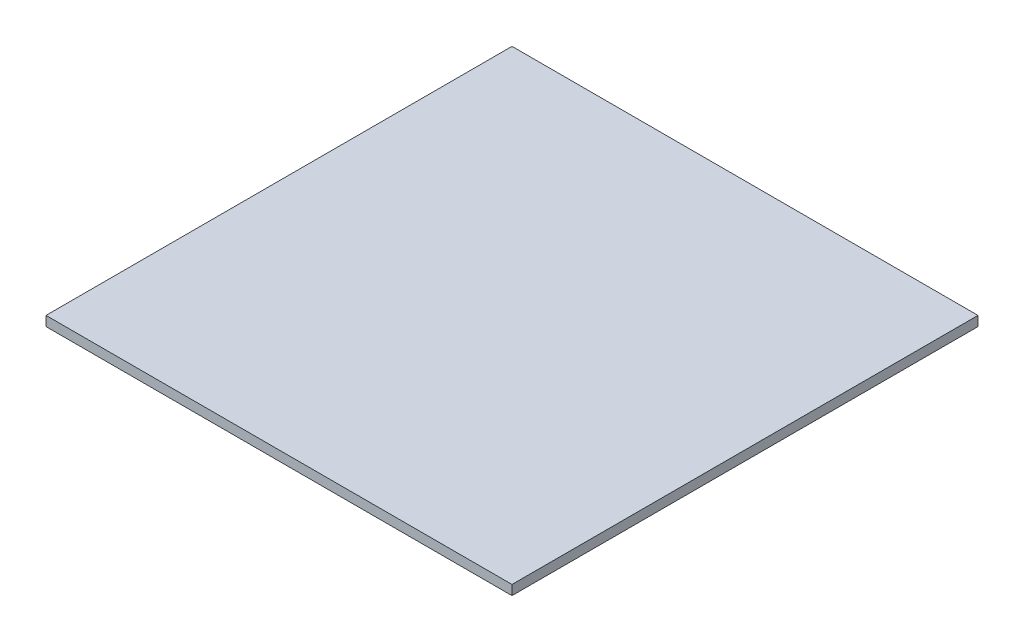
SolidWorks part; units mm, degrees
ref_plane "Front Plane" through (0, 0, 0) normal (0, 0, 1) x (1, 0, 0)
ref_plane "Top Plane" through (0, 0, 0) normal (0, 1, 0) x (1, 0, 0)
ref_plane "Right Plane" through (0, 0, 0) normal (1, 0, 0) x (0, 0, -1)
sketch "Sketch1" plane through (0, 0, 0) normal (0, 0, 1) x (1, 0, 0)
  line L10 (76.2, 1.5875) -> (-76.2, 1.5875)
  line L11 (76.2, 1.5875) -> (76.2, -1.5875)
  line L12 (76.2, -1.5875) -> (-76.2, -1.5875)
  line L13 (-76.2, 1.5875) -> (-76.2, -1.5875)
  line L14 (76.2, 1.5875) -> (-76.2, -1.5875) construction
  line L15 (76.2, -1.5875) -> (-76.2, 1.5875) construction
  point P0 (0, 0)
  dimension "D1" = 3.175
  dimension "D2" = 152.4
extrude "Boss-Extrude1" add sketch "Sketch1" along normal mid plane 152.4
